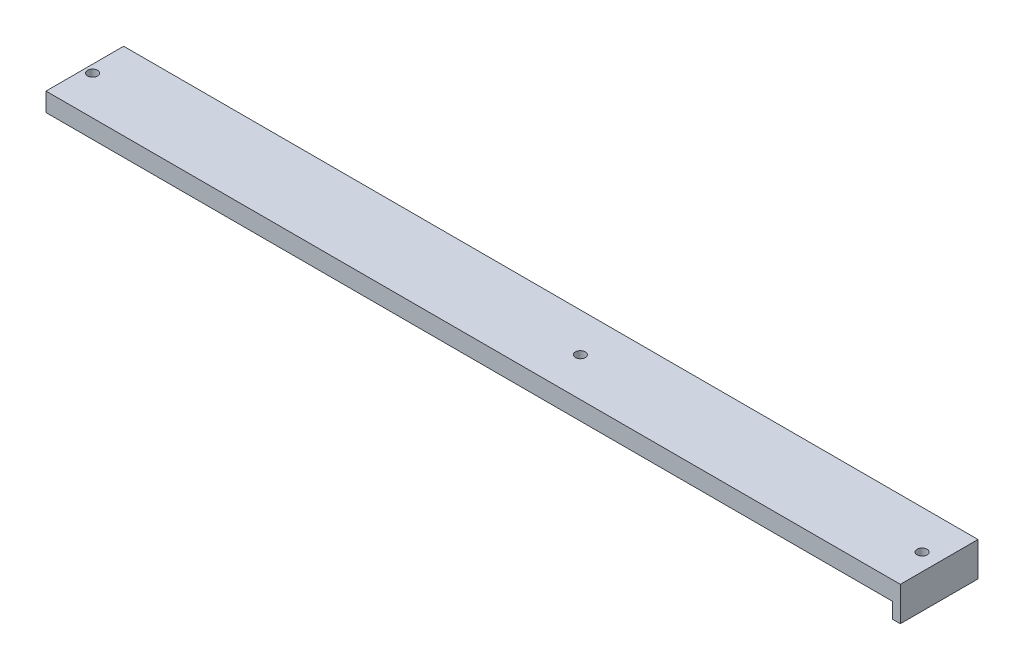
SolidWorks part; units mm, degrees
ref_plane "Front Plane" through (0, 0, 0) normal (0, 0, 1) x (1, 0, 0)
ref_plane "Top Plane" through (0, 0, 0) normal (0, 1, 0) x (1, 0, 0)
ref_plane "Right Plane" through (0, 0, 0) normal (1, 0, 0) x (0, 0, -1)
sketch "Sketch1" plane through (0, 0, 0) normal (0, 1, 0) x (1, 0, 0)
  line L0 (-137.5, 12.5) -> (-132.5, -12.5) construction
  line L1 (-137.5, -12.5) -> (137.5, -12.5)
  line L2 (-137.5, -12.5) -> (-137.5, 12.5)
  line L3 (-137.5, 12.5) -> (137.5, 12.5)
  line L4 (137.5, -12.5) -> (137.5, 12.5)
  line L5 (-137.5, -12.5) -> (137.5, 12.5) construction
  line L6 (-137.5, 12.5) -> (137.5, -12.5) construction
  line L8 (-56.5, -50) -> (-56.5, -37.4542) construction
  line L9 (-132.5, -50) -> (19.5, -50) construction
  circle A0 centre (-135, 0) radius 1.6
  circle A1 centre (22, 0) radius 1.6
  circle A2 centre (132, 0) radius 1.6
  point P0 (0, 0)
  point P18 (132, 0)
  point P19 (-56.5, -50)
  point P20 (0, 0)
  dimension "D4" = 3.2
  dimension "D1" = 275
  dimension "D2" = 25
  dimension "D3" = 5
extrude "Boss-Extrude1" add sketch "Sketch1" along normal blind 6 contours A0 L2 L1 L4 L3 A2 A1
sketch "Sketch2" plane through (0, 0, 0) normal (0, -1, 0) x (-1, 0, 0)
  line L0 (137.5, 12.5) -> (-137.5, 12.5) construction
  line L1 (-137.5, -12.5) -> (-135, -12.5)
  line L2 (-137.5, -12.5) -> (-137.5, 12.5)
  line L3 (-137.5, 12.5) -> (-135, 12.5)
  line L4 (-135, -12.5) -> (-135, 12.5)
  dimension "D1" = 2.5
extrude "Boss-Extrude2" add sketch "Sketch2" along normal blind 5
